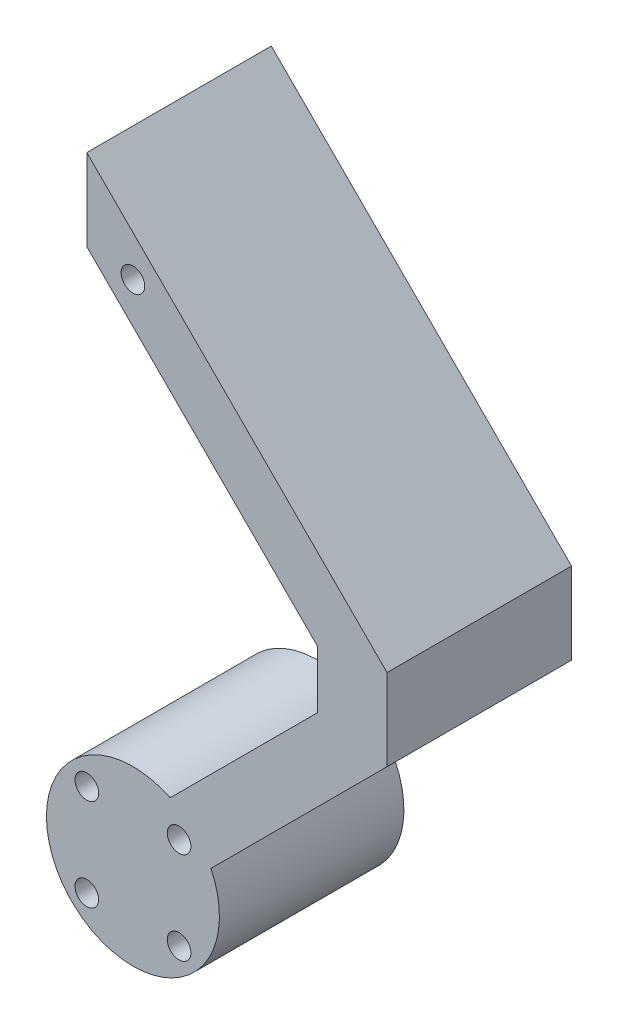
SolidWorks part; units mm, degrees
ref_plane "Front Plane" through (0, 0, 0) normal (0, 0, 1) x (1, 0, 0)
ref_plane "Top Plane" through (0, 0, 0) normal (0, 1, 0) x (1, 0, 0)
ref_plane "Right Plane" through (0, 0, 0) normal (1, 0, 0) x (0, 0, -1)
sketch "Sketch1" plane through (0, 0, 0) normal (0, 0, 1) x (1, 0, 0)
  line L0 (0, -1113.5193) -> (0, -56.7596) construction
  line L1 (40, 6.2731) -> (40, -81877.5303) construction
  line L2 (84.8708, 52.7675) -> (84.8708, -49947.2325) construction
  line L3 (0, 0) -> (50000, 0) construction
  line L4 (-69.8295, 114.8295) -> (35285.5096, -35240.5096) construction
  line L5 (810.5798, -751.4377) -> (59.1421, 0) construction
  line L6 (814.0798, 754.9377) -> (59.1421, 0) construction
  line L7 (-66.3295, -111.3295) -> (-5.5355, -50.5355) construction
  line L8 (0, 45) -> (40, 5)
  line L9 (40, 5) -> (40, -5)
  line L10 (40, -5) -> (14.4645, -30.5355)
  line L11 (0, -56.7596) -> (0, -59.1421)
  line L12 (0, -59.1421) -> (1.5355, -57.6066)
  line L13 (52.0711, 7.0711) -> (0, 59.1421)
  line L14 (0, 59.1421) -> (0, 45)
  line L15 (52.0711, 7.0711) -> (52.0711, -7.0711)
  line L16 (52.0711, 7.0711) -> (-35323.1796, 35382.3217) construction
  line L17 (52.0711, -7.0711) -> (21.5355, -37.6066) construction
  line L18 (8, 51.1421) -> (8, 37) construction
  line L19 (14.4645, -30.5355) -> (35289.0096, 35244.0096) construction
  line L20 (1.5355, -57.6066) -> (-35319.6535, -35378.7957) construction
  line L21 (21.5355, -37.6066) -> (52.0711, -7.0711)
  line L22 (0, -31.3825) -> (0, 29.7417) construction
  line L24 (0, -36.0711) -> (16, -36.0711) construction
  line L25 (0, -36.0711) -> (0, -52.0711) construction
  line L26 (0, -52.0711) -> (16, -52.0711) construction
  line L27 (16, -36.0711) -> (16, -52.0711) construction
  line L28 (0, -36.0711) -> (16, -52.0711) construction
  line L29 (0, -52.0711) -> (16, -36.0711) construction
  circle A0 centre (8, 44.0711) radius 2.05
  arc A2 (14.4645, -30.5355) -> (21.5355, -37.6066) centre (8, -44.0711) ccw
  circle A3 centre (0, -36.0711) radius 2.05
  circle A4 centre (16, -36.0711) radius 2.05
  circle A5 centre (16, -52.0711) radius 2.05
  circle A6 centre (0, -52.0711) radius 2.05
  point P12 (40, 5)
  point P13 (40, 15)
  dimension "D6" = 4.1
  dimension "D8" = 30
  dimension "D1" = 40
  dimension "D2" = 5
  dimension "D3" = 45
  dimension "D4" = 10
  dimension "D5" = 8
  dimension "D7" = 10
  dimension "D9" = 16
  dimension "D10" = 16
extrude "Boss-Extrude2" add sketch "Sketch1" along normal blind 32 contours L10 A2 L21 L15 L13 L14 L8 L9 A6 A5 A4 A3 A0
equation "\"center2edge\"= 40mm"
equation "\"D1@Sketch1\"=\"center2edge\""
equation "\"thick\"= 32mm"
equation "\"width\"= 10mm"
equation "\"D4@Sketch1\"=\"width\""
equation "\"D2@Sketch1\"=\"width\"/2"
equation "\"sh\"= 4.1mm"
equation "\"D6@Sketch1\"=\"sh\""
equation "\"D7@Sketch1\"=\"width\""
equation "\"D1@Boss-Extrude1\"=\"thick\""
equation "\"D1@Sketch2\"=\"thick\""
equation "\"D2@Sketch2\"=\"thick\"-8"
equation "\"D1@Sketch3\"=\"thick\"-8"
equation "\"D2@Sketch3\"=\"thick\""
